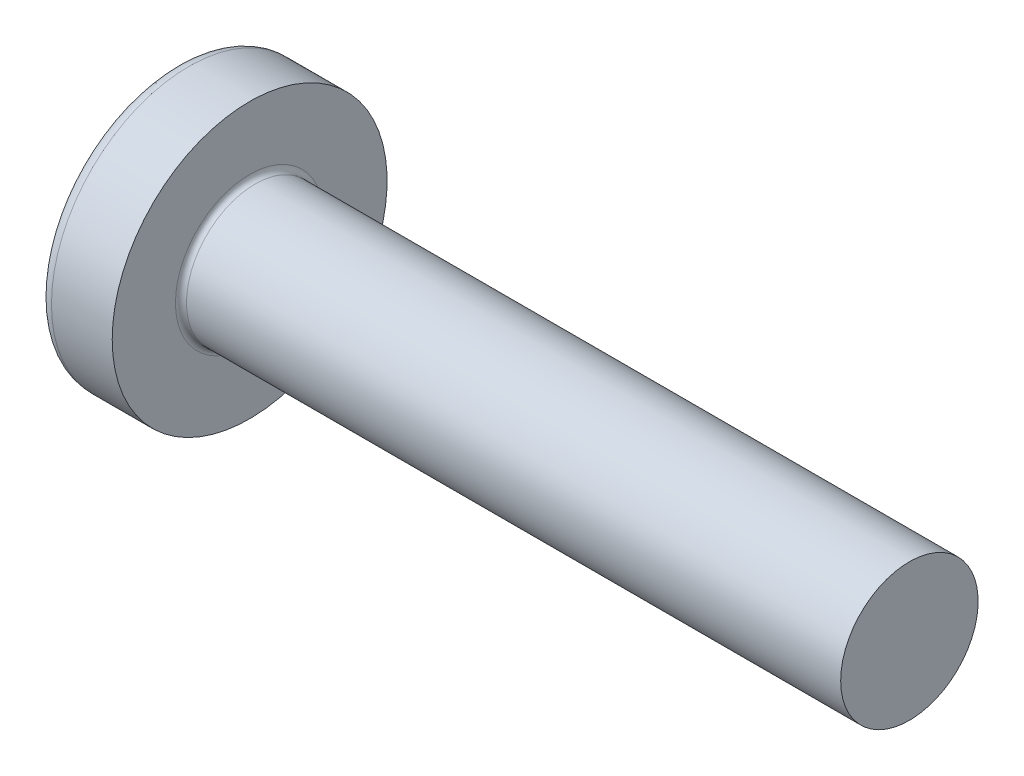
SolidWorks part; units mm, degrees
ref_plane "Plane1" through (0, 0, 0) normal (0, 0, 1) x (1, 0, 0)
ref_plane "Plane2" through (0, 0, 0) normal (0, 1, 0) x (1, 0, 0)
ref_plane "Plane3" through (0, 0, 0) normal (1, 0, 0) x (0, 0, -1)
sketch "BodySke" plane through (0, 0, 0) normal (0, 0, 1) x (1, 0, 0)
  line L0 (2.1, 1.25) -> (2.1, 2.5)
  line L1 (2.325, 6.35) -> (2.325, -3.175) construction
  line L2 (-25.4, 0) -> (127, 0) construction
  line L3 (14.1, 0) -> (0, 0)
  line L4 (2.1, 1.25) -> (14.1, 1.25)
  line L5 (14.1, 1.25) -> (14.1, 0)
  line L6 (0.995, 2.5) -> (2.1, 2.5)
  line L8 (2.1, 6.35) -> (2.1, -3.175) construction
  arc A0 (0.8032, 2.4043) -> (0, 0) centre (4, 0) ccw
  arc A2 (0.8032, 2.4043) -> (0.995, 2.5) centre (0.995, 2.26) cw
  dimension "Head_fillet_rad" = 0.24
  dimension "Head_crown_rad" = 4
  dimension "Head_ht" = 2.1
  dimension "Diameter" = 2.5
  dimension "Length" = 12
  dimension "Head_dia" = 5
  dimension "Advance" = 0.45
  dimension "Thread_nom" = 12
revolve "Base-Revolve" add sketch "BodySke"
cosmetic thread "ThreadCosmetic" [suppressed]
fillet "Fillet1" radius 0.1 1 edges at (2.1, 0, 1.25)
sketch "Sketch3" plane through (0, 0, 0) normal (1, 0, 0) x (0, 0, -1)
  line L0 (0.37, -1.3) -> (-0.37, -1.3)
  line L1 (0.37, -1.3) -> (0.37, 1.3)
  line L2 (-0.37, 1.3) -> (0.37, 1.3)
  line L3 (-0.37, 1.3) -> (-0.37, -1.3)
  dimension "D1" = 1.05
  dimension "Cross_dia" = 2.6
  dimension "D2" = 0.24
  dimension "Cross_width" = 0.74
ref_plane "Plane4" through (1.5, 0, 0) normal (1, 0, 0) x (0, 0, -1)
sketch "Sketch4" plane through (1.5, 0, 0) normal (1, 0, 0) x (0, 0, -1)
  line L0 (0.37, -0.5521) -> (-0.37, -0.5521)
  line L1 (0.37, -0.5521) -> (0.37, 0.5521)
  line L2 (-0.37, 0.5521) -> (0.37, 0.5521)
  line L3 (-0.37, 0.5521) -> (-0.37, -0.5521)
  dimension "D1" = 0.48
  dimension "D2" = 0.684
  dimension "D3" = 0.24
  dimension "D4" = 0.342
loft "Recess" cut profiles "Sketch3", "Sketch4"
pattern_circular "RecPat" count 2 every 90 about axis through (0, 0, 0) along (1, 0, 0) of "Recess"
sketch "RecCorSke" plane through (0, 0, 0) normal (0, 0, 1) x (1, 0, 0)
  line L0 (-3.175, 0) -> (15.875, 0) construction
  line L1 (-25.4, 0) -> (127, 0) construction
  line L2 (0, 0) -> (0, 0.6609)
  line L3 (0, 0.6609) -> (1.5, 0.556)
  line L4 (1.5, 0.556) -> (1.6807, 0)
  line L5 (1.6807, 0) -> (0, 0)
  dimension "Diameter" = 1.112
  dimension "Depth" = 1.42
  dimension "Draft_angle" = 4
  dimension "Bottom_angle" = 18
revolve "RecessCore" cut sketch "RecCorSke" angle 360 about L0
sketch "ThdSchSke" plane through (0, 0, 0) normal (0, 0, 1) x (1, 0, 0)
  line L0 (3, -0.9965) -> (2.8225, -1.25)
  line L1 (3, -0.9965) -> (3.1775, -1.25)
  line L2 (3.1775, -1.25) -> (3.1775, -1.5625)
  line L3 (-3.175, 0) -> (5.1513, 0) construction
  line L5 (3.1775, -1.5625) -> (2.8225, -1.5625)
  line L6 (2.8225, -1.5625) -> (2.8225, -1.25)
  dimension "Thread_minor" = 1.548
  dimension "Diameter" = 2
  dimension "Start" = 2.4
  dimension "SideAngle" = 55
  dimension "VeeAngle" = 70
  dimension "Overcut" = 2.5
revolve "ThreadSchematic" [suppressed] cut sketch "ThdSchSke" angle 360 about L3
pattern_linear "ThdSchPat" [suppressed]
equation "\"D1@Sketch3\" = \"Cross_dia@Sketch3\" / 2"
equation "\"D2@Sketch3\" = \"Cross_width@Sketch3\" / 2"
equation "\"Depth@RecCorSke\" = \"Cross_depth@Plane4\""
equation "\"D1@Sketch4\" = \"Cross_width@Sketch3\""
equation "\"D2@Sketch4\" = \"Cross_dia@Sketch3\" - 2.0 * \"Cross_depth@Plane4\" * tan(26.5  * 0.017453292)"
equation "\"D3@Sketch4\" = \"D1@Sketch4\" / 2"
equation "\"D4@Sketch4\" = \"D2@Sketch4\" / 2"
equation "\"Thread_length@ThreadCosmetic\" = ((sgn( (\"Length@BodySke\" - \"Advance@BodySke\" * 2.0 ) - \"Thread_nom@BodySke\" )-1)*( (\"Length@BodySke\" - \"Advance@BodySke\" * 2.0 ) - \"Thread_nom@BodySke\" ))/-2+ \"Thread_nom@BodySke\""
equation "\"Thread_minor@ThdSchSke\" = \"Thread_minor@ThreadCosmetic\""
equation "\"Diameter@ThdSchSke\" = \"Diameter@BodySke\""
equation "\"Overcut@ThdSchSke\" = \"Diameter@BodySke\" * 1.25"
equation "\"Start@ThdSchSke\" = \"Head_ht@BodySke\" + \"Length@BodySke\" - \"Thread_length@ThreadCosmetic\"  '---Non-countersunk---"
equation "\"Num_threads@ThdSchPat\" = int( \"Thread_length@ThreadCosmetic\" / \"Advance@BodySke\" + 0.999 )  + 1"
equation "\"Advance@ThdSchPat\" = \"Thread_length@ThreadCosmetic\" /  (\"Num_threads@ThdSchPat\" - 1) 'relax it"
